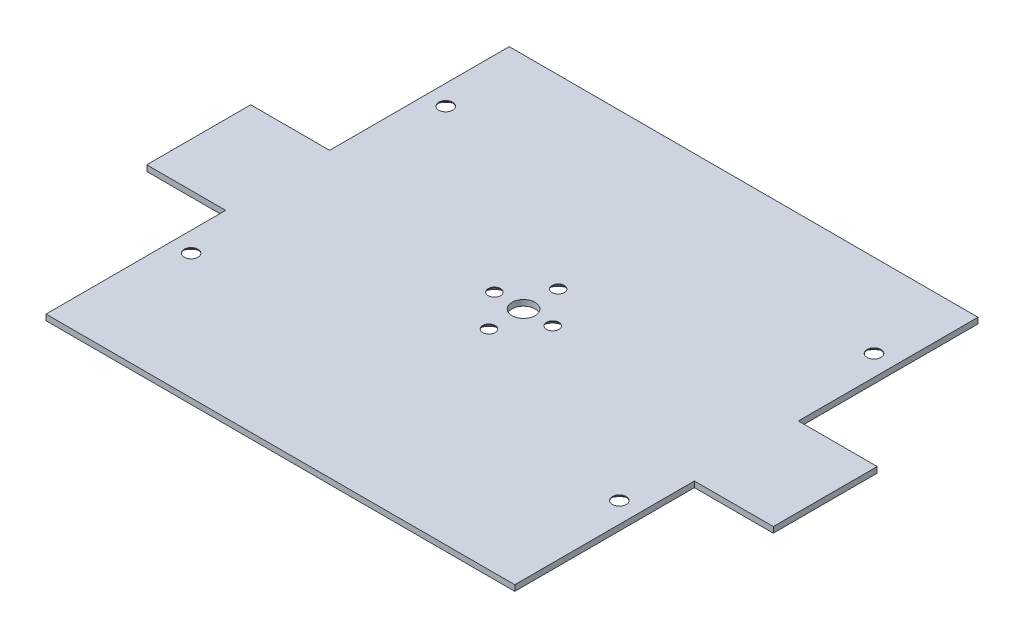
SolidWorks part; units mm, degrees
material "1023 Carbon Steel Sheet (SS)"
ref_plane "Front Plane" through (0, 0, 0) normal (0, 0, 1) x (1, 0, 0)
ref_plane "Top Plane" through (0, 0, 0) normal (0, 1, 0) x (1, 0, 0)
ref_plane "Right Plane" through (0, 0, 0) normal (1, 0, 0) x (0, 0, -1)
sketch "Sketch1" plane through (0, 0, 0) normal (0, 1, 0) x (1, 0, 0)
  line L1 (-64.2938, 63.5317) -> (64.2937, 63.5317)
  line L2 (-85.9314, 14.2557) -> (-85.9314, -14.2558)
  line L3 (-64.2937, -63.5318) -> (64.2938, -63.5318)
  line L4 (85.9314, 14.2558) -> (85.9314, -14.2558)
  line L9 (-85.9314, -14.2558) -> (-64.2937, -14.2558)
  line L10 (-64.2937, -63.5318) -> (-64.2937, -14.2558)
  line L14 (-85.9314, 14.2557) -> (-64.2938, 14.2557)
  line L15 (-64.2938, 63.5317) -> (-64.2938, 14.2557)
  line L18 (85.9314, -14.2558) -> (64.2938, -14.2558)
  line L19 (64.2938, -63.5318) -> (64.2938, -14.2558)
  line L23 (85.9314, 14.2558) -> (64.2938, 14.2557)
  line L24 (64.2937, 63.5317) -> (64.2938, 14.2557)
  dimension "D1" = 128.5875
  dimension "D2" = 28.5115
  dimension "D3" = 21.6376
  dimension "D4" = 49.276
  dimension "D5" = 64.2938
  dimension "D6" = 14.2558
extrude "Boss-Extrude1" add sketch "Sketch1" along normal blind 1.5875
hole_wizard "CSK for #6 Flat Head Machine Screw (100)1" positions "Sketch3" profile "Sketch2" countersink size "#6" standard "ANSI Inch" end condition through all
sketch "Sketch3" plane through (0, 0, 0) normal (0, -1, 0) x (-1, 0, 0)
  point P0 (58.8486, -29.1783)
  point P3 (58.8486, 40.6718)
  point P6 (-58.6264, 40.6718)
  point P9 (-58.6264, -29.1783)
sketch "Sketch2" plane through (-58.8486, 0, 29.1783) normal (1, 0, 0) x (0, 0, -1)
  line L0 (0, 0) -> (0, 1.5875)
  line L1 (0, 1.5875) -> (1.8986, 1.5875)
  line L2 (1.8986, 1.5875) -> (1.8986, 1.38)
  line L3 (1.8986, 1.38) -> (3.5433, 0)
  line L5 (3.5433, 0) -> (0, 0)
  line L6 (-1.8986, 1.38) -> (-3.5433, 0) construction
  line L11 (0, -6.35) -> (0, 107.95) construction
  dimension "Thru Hole Dia." = 3.7973
  dimension "Thru Hole Depth" = 1.5875
  dimension "Near C'Sink Dia." = 7.0866
  dimension "Near C'Sink Angle" = 100
sketch "Sketch4" plane through (0, 0, 0) normal (0, -1, 0) x (1, 0, 0)
  line L0 (64.2937, -63.5317) -> (-64.2938, -63.5317) construction
  line L1 (85.9314, 14.2558) -> (85.9314, -14.2558) construction
  circle A1 centre (0, -3.175) radius 3.175
  dimension "D1" = 6.35
  dimension "D2" = 60.3567
  dimension "D3" = 85.9314
extrude "Cut-Extrude1" cut sketch "Sketch4" against normal through all
hole_wizard "CSK for M3 Flat Head Machine Screw2" positions "Sketch6" profile "Sketch5" countersink size "M3" standard "ANSI Metric" end condition through all
sketch "Sketch6" plane through (0, 0, 0) normal (0, -1, 0) x (-1, 0, 0)
  circle A0 centre (0, 3.175) radius 8 construction
  circle A1 centre (0, 3.175) radius 9.5 construction
  point P7 (-8, 3.175)
  point P9 (8, 3.175)
  point P11 (0, 12.675)
  point P13 (0, -6.325)
  dimension "D1" = 16
  dimension "D2" = 19
sketch "Sketch5" plane through (8, 0, -3.175) normal (1, 0, 0) x (0, 0, -1)
  line L0 (0, 0) -> (0, 1.5875)
  line L1 (0, 1.5875) -> (1.7, 1.5875)
  line L2 (1.7, 1.5875) -> (1.7, 1.45)
  line L3 (1.7, 1.45) -> (3.15, 0)
  line L5 (3.15, 0) -> (0, 0)
  line L6 (-1.7, 1.45) -> (-3.15, 0) construction
  line L11 (0, -6.35) -> (0, 107.95) construction
  dimension "Thru Hole Dia." = 3.4
  dimension "Thru Hole Depth" = 1.5875
  dimension "Near C'Sink Dia." = 6.3
  dimension "Near C'Sink Angle" = 90
equation "\"D6@Sketch1\"=\"D2@Sketch1\"/2"
equation "\"D5@Sketch1\"=\"D1@Sketch1\"/2"
